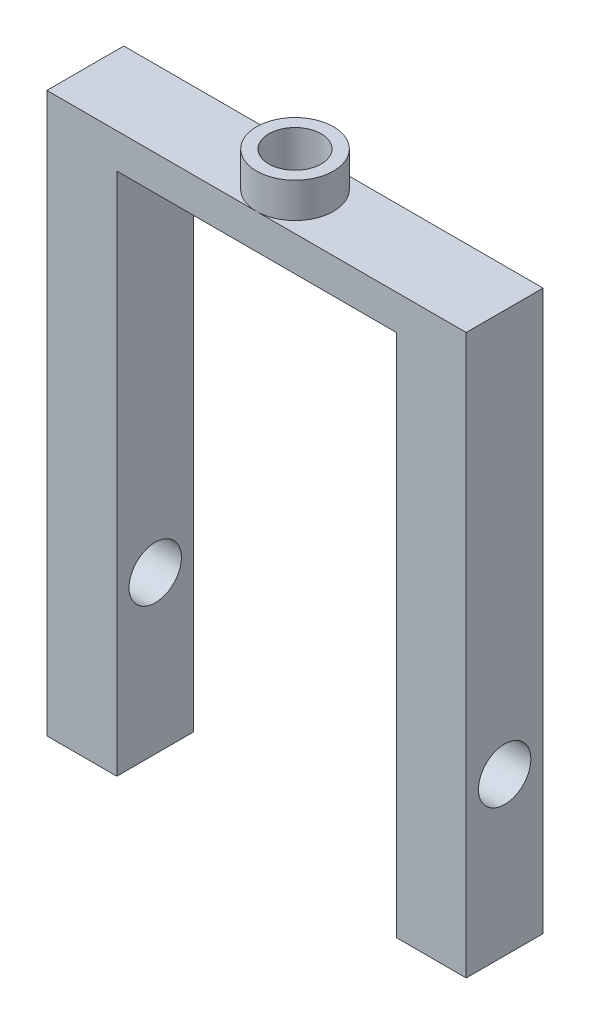
SolidWorks part; units mm, degrees
ref_plane "Front Plane" through (0, 0, 0) normal (0, 0, 1) x (1, 0, 0)
ref_plane "Top Plane" through (0, 0, 0) normal (0, 1, 0) x (1, 0, 0)
ref_plane "Right Plane" through (0, 0, 0) normal (1, 0, 0) x (0, 0, -1)
sketch "Sketch1" plane through (0, 0, 0) normal (0, 1, 0) x (1, 0, 0)
  circle A0 centre (0, 0) radius 6.985
  dimension "D1" = 13.97
extrude "Boss-Extrude1" add sketch "Sketch1" against normal blind 6.35
sketch "Sketch3" plane through (0, 0, 0) normal (0, 1, 0) x (1, 0, 0)
  circle A0 centre (0, 0) radius 4.7625
  circle A1 centre (0, 0) radius 6.985 construction
  dimension "D1" = 9.525
extrude "Cut-Extrude1" cut sketch "Sketch3" against normal blind 63.5
sketch "Sketch5" plane through (0, -6.35, 0) normal (0, -1, 0) x (-1, 0, 0)
  line L1 (38.1, -6.985) -> (-38.1, -6.985)
  line L2 (38.1, -6.985) -> (38.1, 6.985)
  line L3 (38.1, 6.985) -> (-38.1, 6.985)
  line L4 (-38.1, -6.985) -> (-38.1, 6.985)
  line L5 (38.1, -6.985) -> (-38.1, 6.985) construction
  line L6 (38.1, 6.985) -> (-38.1, -6.985) construction
  circle A0 centre (0, 0) radius 4.7625 construction
  point P0 (0, 0)
  dimension "D1" = 76.2
  dimension "D2" = 13.97
extrude "Boss-Extrude2" add sketch "Sketch5" along normal blind 101.6
sketch "Sketch6" plane through (0, 0, -6.985) normal (0, 0, -1) x (-1, 0, 0)
  line L0 (0, -6.35) -> (-38.1, -6.35) construction
  line L1 (25.4, -12.7) -> (-25.4, -12.7)
  line L2 (25.4, -12.7) -> (25.4, -107.95)
  line L3 (25.4, -107.95) -> (-25.4, -107.95)
  line L4 (-25.4, -12.7) -> (-25.4, -107.95)
  line L5 (25.4, -12.7) -> (-25.4, -107.95) construction
  line L6 (25.4, -107.95) -> (-25.4, -12.7) construction
  line L7 (38.1, -107.95) -> (38.1, -6.35) construction
  line L8 (38.1, -107.95) -> (-38.1, -107.95) construction
  point P0 (0, -64.4831)
  point P14 (0, -60.325)
  dimension "D1" = 50.8
  dimension "D3" = 6.35
  dimension "D4" = 38.1
extrude "Cut-Extrude2" cut sketch "Sketch6" against normal through all
sketch "Sketch7" plane through (0, 0, 0) normal (0, 1, 0) x (1, 0, 0)
  circle A0 centre (0, 0) radius 4.7625
  dimension "D1" = 9.525
extrude "Cut-Extrude3" cut sketch "Sketch7" against normal through all
sketch "Sketch8" plane through (25.4, 0, 0) normal (-1, 0, 0) x (0, 0, 1)
  line L0 (6.985, -12.7) -> (-6.985, -12.7) construction
  line L1 (-6.985, -12.7) -> (-6.985, -107.95) construction
  circle A0 centre (0, -79.375) radius 4.7625
  dimension "D1" = 9.525
  dimension "D2" = 66.675
  dimension "D3" = 6.985
extrude "Cut-Extrude4" cut sketch "Sketch8" against normal blind 19.05 and the other way through all
